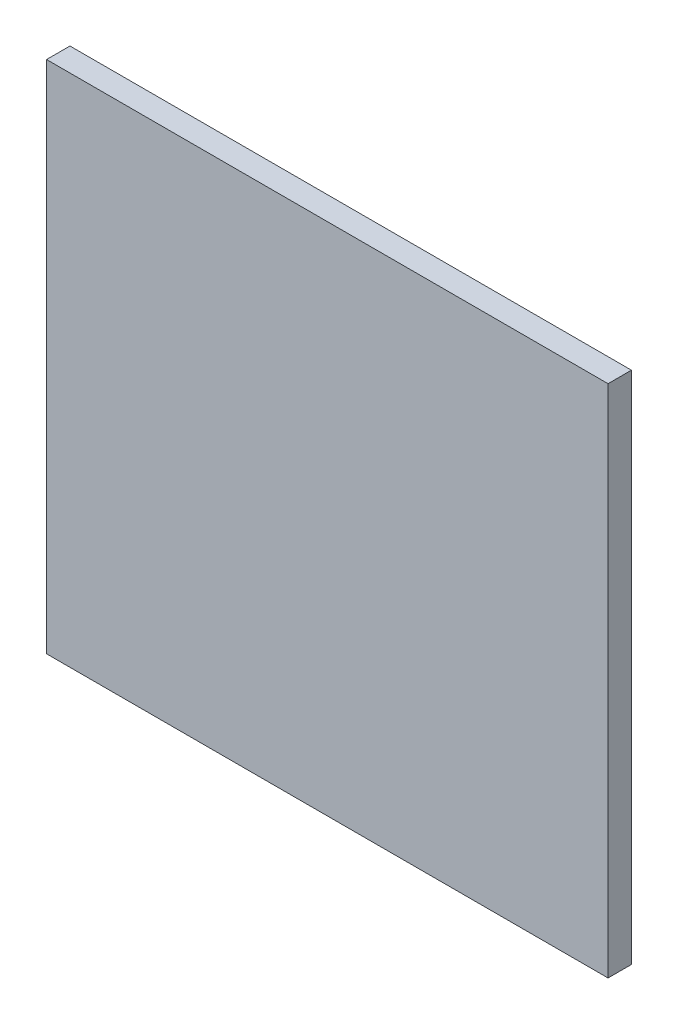
SolidWorks part; units mm, degrees
ref_plane "Front Plane" through (0, 0, 0) normal (0, 0, 1) x (1, 0, 0)
ref_plane "Top Plane" through (0, 0, 0) normal (0, 1, 0) x (1, 0, 0)
ref_plane "Right Plane" through (0, 0, 0) normal (1, 0, 0) x (0, 0, -1)
sketch "Sketch1" plane through (0, 0, 0) normal (0, 0, 1) x (1, 0, 0)
  line L0 (0, 69.85) -> (0, -69.85) construction
  line L1 (-76.2, -69.85) -> (76.2, -69.85)
  line L2 (-76.2, -69.85) -> (-76.2, 69.85)
  line L3 (-76.2, 69.85) -> (76.2, 69.85)
  line L4 (76.2, -69.85) -> (76.2, 69.85)
  line L5 (-76.2, -69.85) -> (76.2, 69.85) construction
  line L6 (-76.2, 69.85) -> (76.2, -69.85) construction
  line L7 (-76.2, 0) -> (76.2, 0) construction
  point P0 (0, 0)
  point P8 (0, 0)
  dimension "D1" = 139.7
  dimension "D2" = 152.4
extrude "Boss-Extrude1" add sketch "Sketch1" along normal blind 6.35
